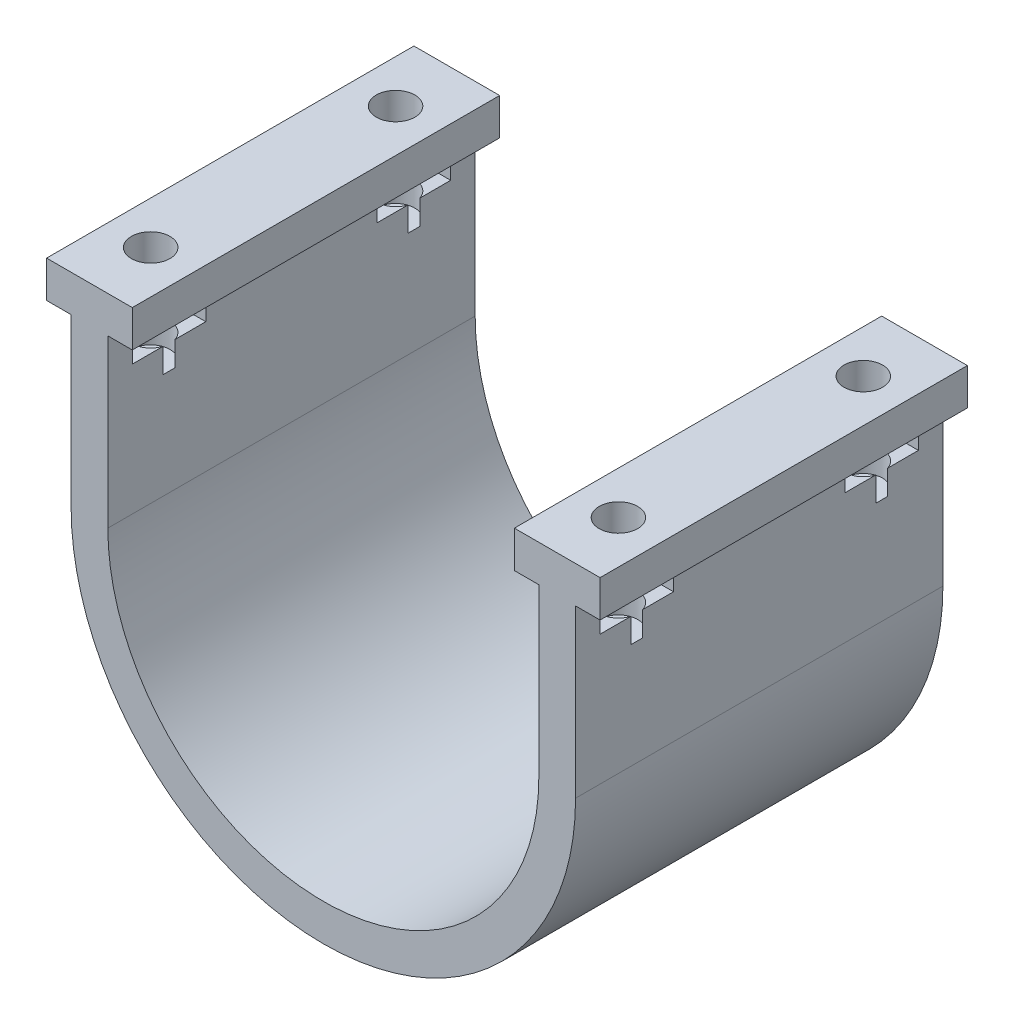
SolidWorks part; units mm, degrees
ref_plane "Front Plane" through (0, 0, 0) normal (0, 0, 1) x (1, 0, 0)
ref_plane "Top Plane" through (0, 0, 0) normal (0, 1, 0) x (1, 0, 0)
ref_plane "Right Plane" through (0, 0, 0) normal (1, 0, 0) x (0, 0, -1)
other "Configuration Table"
sketch "Sketch1" plane through (0, 0, 0) normal (0, 0, 1) x (1, 0, 0)
  line L0 (-22.352, 0) -> (-22.352, 17.272)
  line L1 (-19.812, 21.082) -> (-28.702, 21.082)
  line L2 (-28.702, 21.082) -> (-28.702, 17.272)
  line L3 (-28.702, 17.272) -> (-26.162, 17.272)
  line L4 (-26.162, 17.272) -> (-26.162, 0)
  line L5 (26.162, 0) -> (26.162, 17.272)
  line L6 (26.162, 17.272) -> (28.702, 17.272)
  line L7 (28.702, 17.272) -> (28.702, 21.082)
  line L8 (28.702, 21.082) -> (19.812, 21.082)
  line L9 (22.352, 17.272) -> (22.352, 0)
  line L10 (0, 22.352) -> (-46.8793, 22.352) construction
  line L11 (-22.352, 17.272) -> (-19.812, 17.272)
  line L12 (-19.812, 17.272) -> (-19.812, 21.082)
  line L13 (22.352, 17.272) -> (19.812, 17.272)
  line L14 (19.812, 17.272) -> (19.812, 21.082)
  circle A0 centre (0, 0) radius 22.352 construction
  arc A1 (-22.352, 0) -> (22.352, 0) centre (0, 0) ccw
  arc A2 (-26.162, 0) -> (26.162, 0) centre (0, 0) ccw
  point P22 (19.3943, 19.812)
  dimension "D1" = 44.704
  dimension "D2" = 1.27
  dimension "D3" = 3.81
  dimension "D4" = 3.81
  dimension "D5" = 2.54
  dimension "D6" = 2.54
extrude "Boss-Extrude1" add sketch "Sketch1" along normal mid plane 38.1
sketch "Sketch2" plane through (0, 21.082, 0) normal (0, 1, 0) x (1, 0, 0)
  line L0 (-28.702, -19.05) -> (-28.702, 19.05) construction
  line L2 (24.257, 12.7) -> (-24.257, 12.7) construction
  line L3 (24.257, 12.7) -> (24.257, -12.7) construction
  line L4 (24.257, -12.7) -> (-24.257, -12.7) construction
  line L5 (-24.257, 12.7) -> (-24.257, -12.7) construction
  line L6 (24.257, 12.7) -> (-24.257, -12.7) construction
  line L7 (24.257, -12.7) -> (-24.257, 12.7) construction
  circle A0 centre (-24.257, 12.7) radius 2
  circle A1 centre (-24.257, -12.7) radius 2
  circle A2 centre (24.257, -12.7) radius 2
  circle A3 centre (24.257, 12.7) radius 2
  point P0 (28.4609, -12.7)
  point P11 (0, 0)
  dimension "D2" = 4
  dimension "D1" = 25.4
  dimension "D3" = 4.445
extrude "Cut-Extrude1" cut sketch "Sketch2" against normal blind 10.16
sketch "Sketch3" plane through (-26.162, 0, 0) normal (-1, 0, 0) x (0, 0, 1)
  line L0 (19.05, 17.272) -> (-19.05, 17.272) construction
  line L1 (-8.89, 17.272) -> (-16.51, 17.272)
  line L2 (-8.89, 17.272) -> (-8.89, 13.462)
  line L3 (-8.89, 13.462) -> (-16.51, 13.462)
  line L4 (-16.51, 17.272) -> (-16.51, 13.462)
  line L5 (-8.89, 17.272) -> (-16.51, 13.462) construction
  line L6 (-8.89, 13.462) -> (-16.51, 17.272) construction
  line L7 (16.51, 17.272) -> (8.89, 17.272)
  line L8 (16.51, 17.272) -> (16.51, 13.462)
  line L9 (16.51, 13.462) -> (8.89, 13.462)
  line L10 (8.89, 17.272) -> (8.89, 13.462)
  line L11 (16.51, 17.272) -> (8.89, 13.462) construction
  line L12 (16.51, 13.462) -> (8.89, 17.272) construction
  point P0 (-12.7, 15.367)
  point P5 (12.7, 15.367)
  point P15 (-21.3301, 27.3366)
  dimension "D1" = 12.7
  dimension "D2" = 12.7
  dimension "D3" = 7.62
  dimension "D4" = 3.81
extrude "Cut-Extrude2" cut sketch "Sketch3" against normal through all
